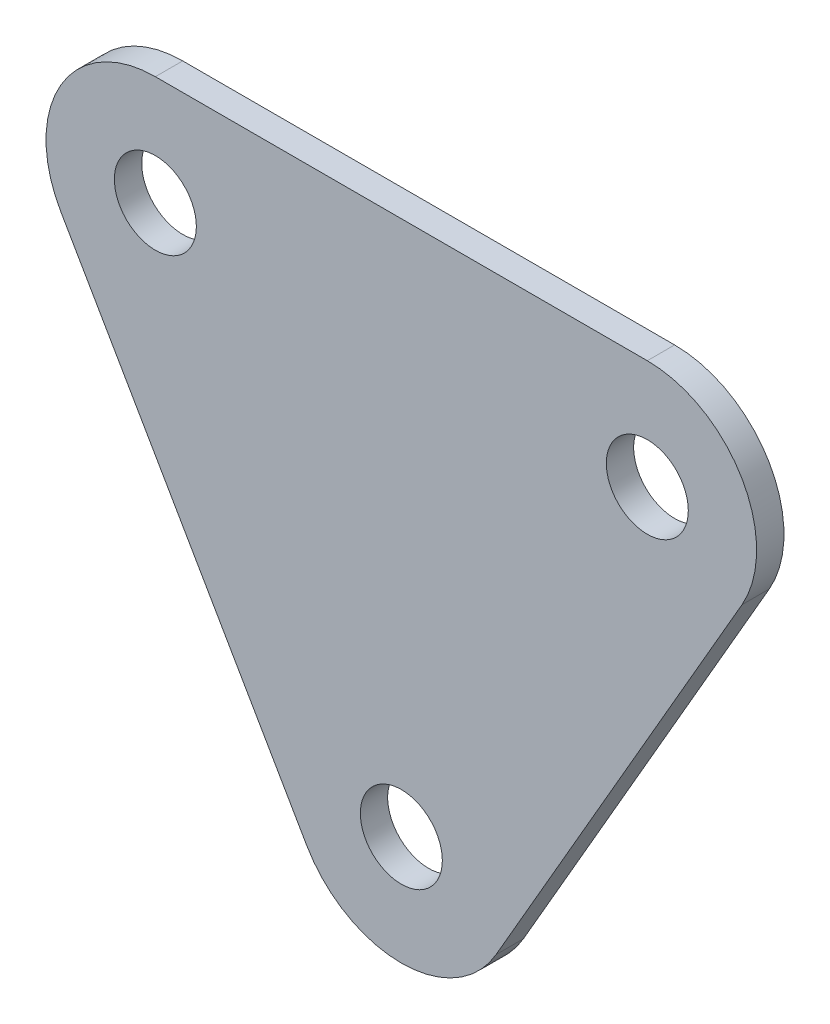
SolidWorks part; units mm, degrees
ref_plane "Front Plane" through (0, 0, 0) normal (0, 0, 1) x (1, 0, 0)
ref_plane "Top Plane" through (0, 0, 0) normal (0, 1, 0) x (1, 0, 0)
ref_plane "Right Plane" through (0, 0, 0) normal (1, 0, 0) x (0, 0, -1)
sketch "Sketch1" plane through (0, 0, 0) normal (0, 0, 1) x (1, 0, 0)
  line L0 (0, 0) -> (360, 0)
  line L1 (429.282, -120) -> (249.282, -431.7691)
  line L2 (110.718, -431.7691) -> (-69.282, -120)
  arc A0 (360, 0) -> (429.282, -120) centre (360, -80) cw
  arc A1 (249.282, -431.7691) -> (110.718, -431.7691) centre (180, -391.7691) cw
  arc A2 (-69.282, -120) -> (0, 0) centre (0, -80) cw
  circle A3 centre (0, -80) radius 30
  circle A4 centre (360, -80) radius 30
  circle A5 centre (180, -391.7691) radius 30
  dimension "D2" = 80
  dimension "D3" = 360
  dimension "D5" = 80
  dimension "D6" = 80
  dimension "D1" = 360
  dimension "D4" = 360
extrude "Boss-Extrude1" add sketch "Sketch1" along normal blind 20
